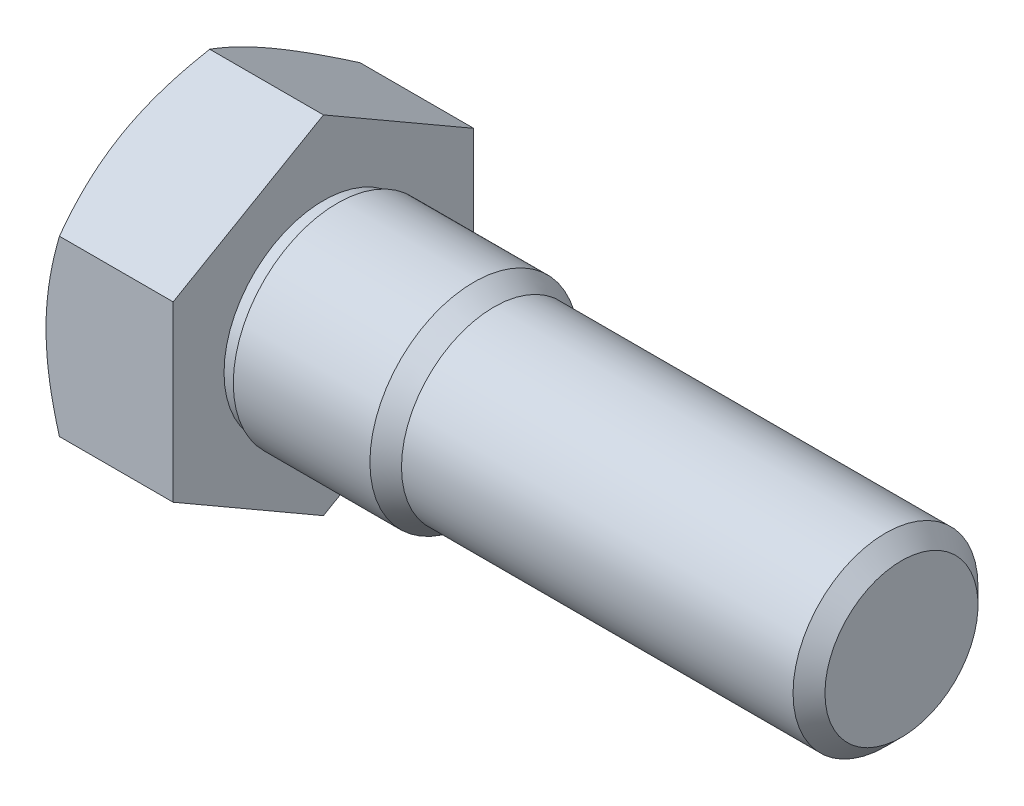
SolidWorks part; units mm, degrees
ref_plane "Front Plane" through (0, 0, 0) normal (0, 0, 1) x (1, 0, 0)
ref_plane "Top Plane" through (0, 0, 0) normal (0, 1, 0) x (1, 0, 0)
ref_plane "Right Plane" through (0, 0, 0) normal (1, 0, 0) x (0, 0, -1)
other "Configuration Table"
sketch "BaseHeadSke" plane through (0, 0, 0) normal (1, 0, 0) x (0, 0, -1)
  line L1 (0, 7.5056) -> (-6.5, 3.7528)
  line L2 (-6.5, 3.7528) -> (-6.5, -3.7528)
  line L3 (-6.5, -3.7528) -> (0, -7.5056)
  line L4 (0, -7.5056) -> (6.5, -3.7528)
  line L5 (6.5, -3.7528) -> (6.5, 3.7528)
  line L6 (6.5, 3.7528) -> (0, 7.5056)
  circle A0 centre (0, 0) radius 6.5 construction
  dimension "Width_flats" = 13
extrude "BaseHead" add sketch "BaseHeadSke" along normal blind 5.5
sketch "HeadChamferSke" plane through (0, 0, 0) normal (0, 0, 1) x (1, 0, 0)
  line L0 (0, 0) -> (36.4787, 0) construction
  line L1 (0, 3.7528) -> (0, -3.7528) construction
  line L2 (0, 7.5056) -> (0, 6.5)
  line L3 (0, 6.5) -> (0.5806, 7.5056)
  line L4 (0.5806, 7.5056) -> (0, 7.5056)
  line L7 (5.5, 7.5056) -> (0, 7.5056) construction
  dimension "Angle_Chamfer_Head" = 30
revolve "HeadChamfer" cut sketch "HeadChamferSke" angle 360 about L0
sketch "BodySke" plane through (0, 0, 0) normal (0, 0, 1) x (1, 0, 0)
  line L0 (0, 0) -> (144.9862, 0) construction
  line L1 (5.5, 4.3) -> (6.1, 4.3)
  line L2 (5.5, 3.7528) -> (5.5, -3.7528) construction
  line L3 (6.1, 4.3) -> (6.1, 4.5)
  line L4 (6.1, 4.5) -> (12.009, 4.5)
  line L5 (12.009, 4.5) -> (12.875, 4)
  line L6 (12.875, 4) -> (29.8095, 4)
  line L7 (29.8095, 4) -> (30.5, 3.3095)
  line L8 (30.5, 3.3095) -> (30.5, 0)
  line L9 (30.5, 0) -> (5.5, 0)
  line L10 (5.5, 0) -> (5.5, 4.3)
  line L11 (6.75, 0) -> (6.75, 23.2443) construction
  line L12 (16, 0) -> (16, 26.3648) construction
  dimension "Diameter_nothread" = 9
  dimension "Diameter" = 8
  dimension "Length" = 25
  dimension "Thread_minor" = 6.619
  dimension "Body_Chamfer_Angle" = 45
  dimension "Angle" = 30
  dimension "Groove_height" = 0.2
  dimension "Reliff_groove" = 0.6
  dimension "Advance" = 1.25
  dimension "Thread_length" = 14.5
  dimension "D3" = 3.125
revolve "BaseBody" add sketch "BodySke" angle 360 about L0
cosmetic thread "ThreadCosmetic" [suppressed] parameters "Thread_length"=14.5, "Thread_minor"=6.619
sketch "ThdSchSke" plane through (0, 0, 0) normal (0, 0, 1) x (1, 0, 0)
  line L0 (0, 0) -> (125.7008, 0) construction
  line L1 (28.5595, 4.7973) -> (28.5595, 4)
  line L2 (28.5595, 4.7973) -> (29.3568, 4.7973)
  line L3 (29.3568, 4.7973) -> (29.3568, 4)
  line L4 (29.3568, 4) -> (28.9582, 3.3095)
  line L5 (28.9582, 3.3095) -> (28.5595, 4)
  dimension "D1" = 1.25
revolve "ThreadSchematic" [suppressed] cut sketch "ThdSchSke" angle 360 about L0
pattern_linear "ThdSchPat" [suppressed]
sketch "Sketch12" plane through (30.5, 0, 0) normal (1, 0, 0) x (0, 0, -1)
  circle A0 centre (0, 0) radius 4 construction
  circle A1 centre (0, 0) radius 4
  circle A2 centre (0, 0) radius 4
sketch "Sketch14" plane through (30.5, 0, 0) normal (1, 0, 0) x (0, 0, -1)
  circle A0 centre (0, 0) radius 4 construction
  circle A1 centre (0, 0) radius 4
curve "Helix/Spiral1" pitch 1.25 height 15 turns 12
equation "\"D3@BodySke\" = \"Advance@BodySke\" * 2.5"
equation "\"Thread_length@ThreadCosmetic\" = \"Thread_length@BodySke\""
equation "\"Thread_minor@ThreadCosmetic\" = \"Thread_minor@BodySke\""
equation "\"D1@ThdSchSke\" = \"Advance@BodySke\""
equation "\"Tooth_Num@ThdSchPat\" =  int( \"Thread_length@BodySke\" / \"Advance@BodySke\" ) - 1 "
equation "\"Advance@ThdSchPat\" = \"Advance@BodySke\""
